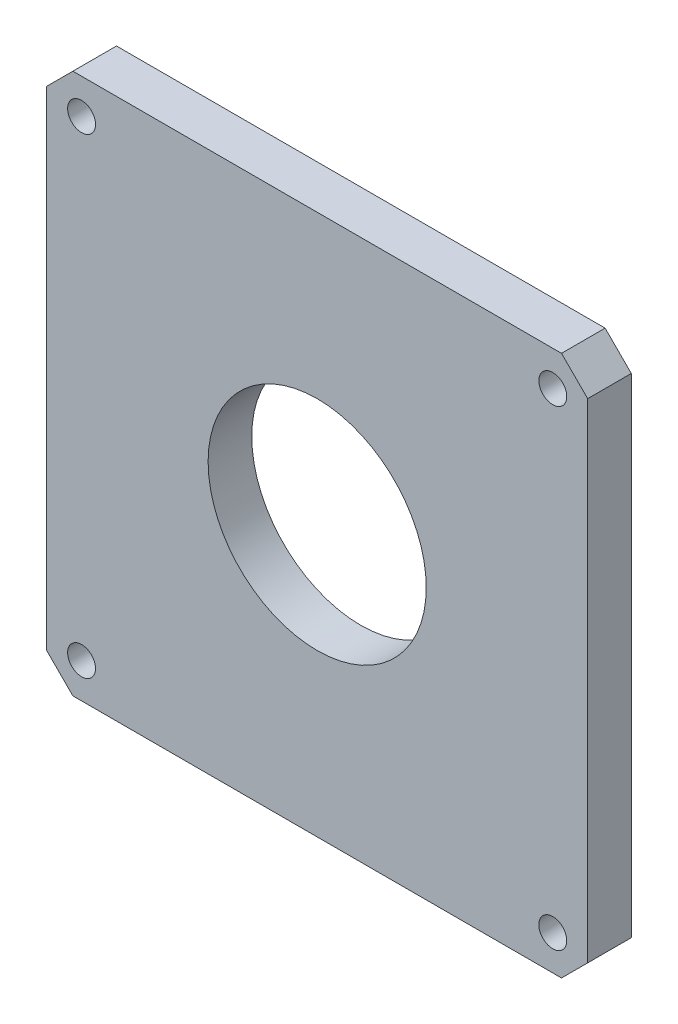
SolidWorks part; units mm, degrees
ref_plane "正面" through (0, 0, 0) normal (0, 0, 1) x (1, 0, 0)
ref_plane "平面" through (0, 0, 0) normal (0, 1, 0) x (1, 0, 0)
ref_plane "右側面" through (0, 0, 0) normal (1, 0, 0) x (0, 0, -1)
sketch "ｽｹｯﾁ1" plane through (0, 0, 0) normal (0, 0, 1) x (1, 0, 0)
  line L0 (31, 0) -> (-31, 0) construction
  line L1 (-31, 31) -> (31, 31)
  line L2 (-31, 31) -> (-31, -31)
  line L3 (-31, -31) -> (31, -31)
  line L4 (31, 31) -> (31, -31)
  circle A0 centre (0, 0) radius 12.5
  dimension "D2" = 25
  dimension "D1" = 62
extrude "ﾎﾞｽ - 押し出し1" add sketch "ｽｹｯﾁ1" along normal blind 5
chamfer "面取り1" distance 3 angle 45 4 edges at (31, -31, 2.5) (31, 31, 2.5) (-31, 31, 2.5) (-31, -31, 2.5)
sketch "ｽｹｯﾁ2" plane through (0, 0, 5) normal (0, 0, 1) x (1, 0, 0)
  line L0 (0, 0) -> (7.6596, 0) construction
  line L2 (0, 8.53) -> (0, 0) construction
  line L3 (-27, 27) -> (27, 27) construction
  line L4 (27, 27) -> (27, -27) construction
  circle A0 centre (27, 27) radius 1.6
  circle A1 centre (-27, 27) radius 1.6
  circle A2 centre (27, -27) radius 1.6
  circle A3 centre (-27, -27) radius 1.6
  dimension "D1" = 54
  dimension "D2" = 3.2
extrude "ｶｯﾄ - 押し出し1" cut sketch "ｽｹｯﾁ2" against normal through all
